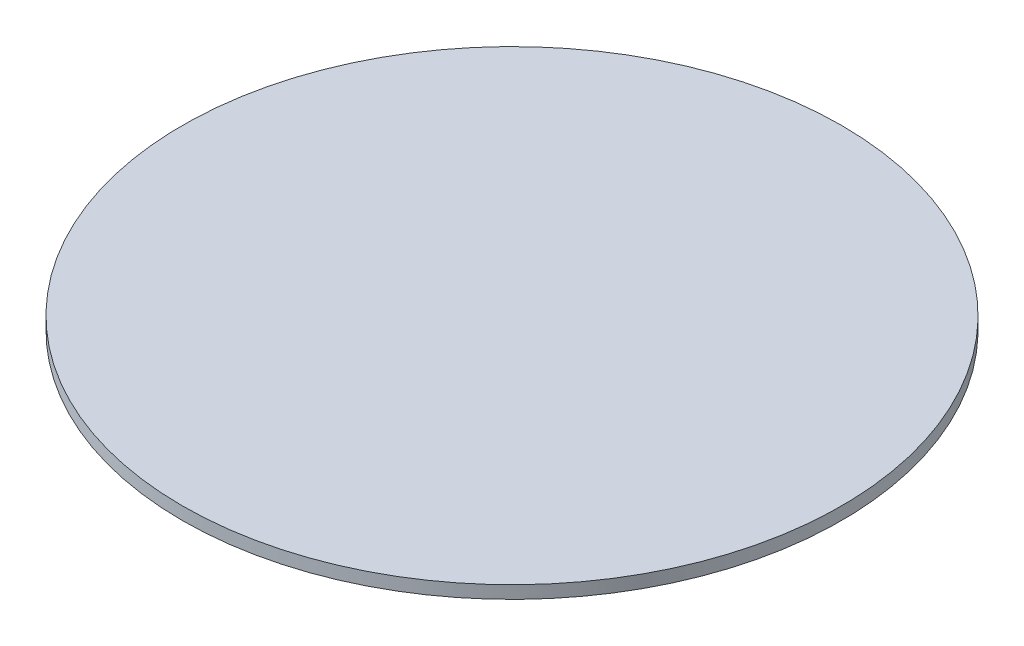
SolidWorks part; units mm, degrees
ref_plane "Front Plane" through (0, 0, 0) normal (0, 0, 1) x (1, 0, 0)
ref_plane "Top Plane" through (0, 0, 0) normal (0, 1, 0) x (1, 0, 0)
ref_plane "Right Plane" through (0, 0, 0) normal (1, 0, 0) x (0, 0, -1)
sketch "Sketch1" plane through (0, 0, 0) normal (0, 1, 0) x (1, 0, 0)
  circle A0 centre (0, 0) radius 65.7698
extrude "Boss-Extrude1" add sketch "Sketch1" along normal blind 2.54
